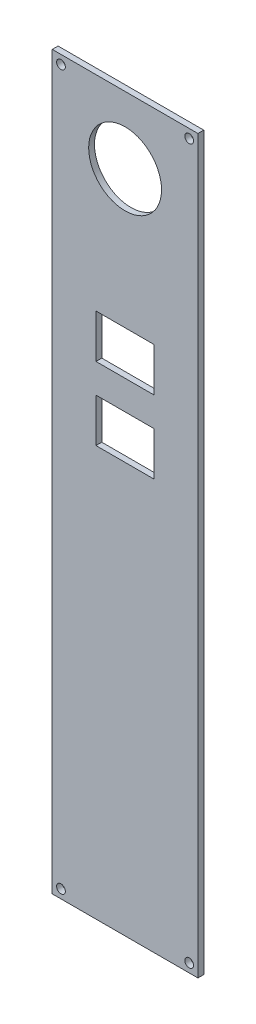
SolidWorks part; units mm, degrees
ref_plane "Front Plane" through (0, 0, 0) normal (0, 0, 1) x (1, 0, 0)
ref_plane "Top Plane" through (0, 0, 0) normal (0, 1, 0) x (1, 0, 0)
ref_plane "Right Plane" through (0, 0, 0) normal (1, 0, 0) x (0, 0, -1)
sketch "Sketch1" plane through (0, 15.2538, 0) normal (0, 0, 1) x (1, 0, 0)
  line L1 (25, -126) -> (-25, -126)
  line L2 (25, -126) -> (25, 125)
  line L3 (25, 125) -> (-25, 125)
  line L4 (-25, -126) -> (-25, 125)
  line L5 (25, -126) -> (-25, 125) construction
  line L6 (25, 125) -> (-25, -126) construction
  point P0 (0, -0.5)
  dimension "D1" = 251
  dimension "D2" = 50
extrude "Boss-Extrude1" add sketch "Sketch1" along normal blind 2 contours L3 L4 L1 L2
sketch "Sketch2" plane through (0, 15.2538, 0) normal (0, 0, -1) x (-1, 0, 0)
  line L0 (-25, -126) -> (-25, 125) construction
  line L1 (-25, 125) -> (25, 125) construction
  circle A0 centre (0, 102) radius 12.5
  point P2 (0, 125)
  dimension "D1" = 25
  dimension "D2" = 23
extrude "Cut-Extrude1" cut sketch "Sketch2" against normal up to next
sketch "Sketch6" plane through (0, 15.2538, 2) normal (0, 0, 1) x (1, 0, 0)
  line L0 (-25, -126) -> (-25, 125) construction
  line L1 (25, 125) -> (-25, 125) construction
  line L2 (25, -126) -> (25, 125) construction
  line L3 (25, -126) -> (-25, -126) construction
  circle A0 centre (-22, 122) radius 1.5
  circle A1 centre (22, 122) radius 1.5
  circle A2 centre (-22, -123) radius 1.5
  circle A3 centre (22, -123) radius 1.5
  dimension "D1" = 3
  dimension "D2" = 3
  dimension "D3" = 3
  dimension "D4" = 3
  dimension "D5" = 3
  dimension "D6" = 3
  dimension "D7" = 3
  dimension "D8" = 3
  dimension "D9" = 3
  dimension "D10" = 3
  dimension "D11" = 3
  dimension "D12" = 3
extrude "Cut-Extrude5" cut sketch "Sketch6" against normal blind 2
sketch "Sketch8" plane through (0, 0, 0) normal (0, 0, -1) x (-1, 0, 0)
  line L0 (-25, -110.7462) -> (-25, 140.2538) construction
  line L1 (10, 55) -> (-10, 55)
  line L2 (10, 55) -> (10, 70)
  line L3 (10, 70) -> (-10, 70)
  line L4 (-10, 55) -> (-10, 70)
  line L5 (10, 55) -> (-10, 70) construction
  line L6 (10, 70) -> (-10, 55) construction
  line L7 (10, 30) -> (-10, 30)
  line L8 (10, 30) -> (10, 45)
  line L9 (10, 45) -> (-10, 45)
  line L10 (-10, 30) -> (-10, 45)
  line L11 (10, 30) -> (-10, 45) construction
  line L12 (10, 45) -> (-10, 30) construction
  point P0 (0, 62.5)
  point P5 (0, 37.5)
  dimension "D1" = 20
  dimension "D2" = 15
  dimension "D3" = 20
  dimension "D4" = 15
  dimension "D5" = 10
  dimension "D6" = 15
  dimension "D7" = 15
  dimension "D8" = 30
extrude "Cut-Extrude6" cut sketch "Sketch8" against normal blind 2
